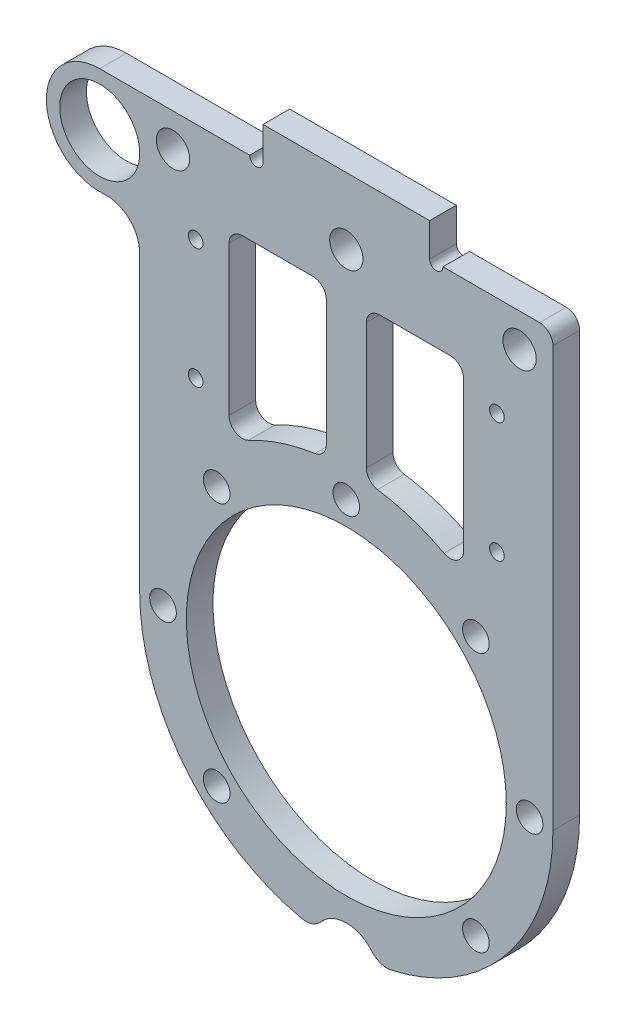
SolidWorks part; units mm, degrees
material "Thornel Mat VMA"
ref_plane "前视基准面" through (0, 0, 0) normal (0, 0, 1) x (1, 0, 0)
ref_plane "上视基准面" through (0, 0, 0) normal (0, 1, 0) x (1, 0, 0)
ref_plane "右视基准面" through (0, 0, 0) normal (1, 0, 0) x (0, 0, -1)
sketch "草图1" plane through (0, 0, 0) normal (0, 0, 1) x (1, 0, 0)
  line L0 (-31, 0) -> (-31, 44.0385)
  line L1 (-37, 65) -> (-12.5, 65)
  line L2 (31, 65) -> (31, 0)
  line L3 (0, 70) -> (0, -32.5) construction
  line L8 (12.5, 65) -> (31, 65)
  line L10 (-12.5, 65) -> (-12.5, 70)
  line L11 (-12.5, 70) -> (12.5, 70)
  line L12 (12.5, 65) -> (12.5, 70)
  line L13 (-26, 60) -> (26, 60) construction
  line L15 (-22.6, 50) -> (22.6, 50) construction
  line L16 (-22.6, 50) -> (-22.6, 32) construction
  line L17 (-22.6, 32) -> (22.6, 32) construction
  line L18 (22.6, 50) -> (22.6, 32) construction
  circle A0 centre (0, 0) radius 24
  arc A1 (-31, 0) -> (-6.7562, -30.2548) centre (0, 0) ccw
  circle A2 centre (0, 0) radius 27.5 construction
  circle A3 centre (-19.4454, 19.4454) radius 2
  circle A4 centre (0, 27.5) radius 2
  circle A5 centre (19.4454, 19.4454) radius 2
  circle A6 centre (27.5, 0) radius 2
  arc A7 (3.814, -29.2668) -> (-3.814, -29.2668) centre (0, -32.5) ccw
  arc A8 (6.7562, -30.2548) -> (31, 0) centre (0, 0) ccw
  arc A9 (3.814, -29.2668) -> (6.7562, -30.2548) centre (6.1024, -27.3269) ccw
  arc A10 (-3.814, -29.2668) -> (-6.7562, -30.2548) centre (-6.1024, -27.3269) cw
  circle A11 centre (19.4454, -19.4454) radius 2
  circle A12 centre (0, -27.5) radius 2 construction
  circle A13 centre (-19.4454, -19.4454) radius 2
  circle A14 centre (-27.5, 0) radius 2
  circle A15 centre (-26, 60) radius 2.5
  circle A16 centre (0, 60) radius 2.5
  circle A17 centre (26, 60) radius 2.5
  circle A18 centre (-22.6, 50) radius 1.1
  circle A19 centre (-22.6, 32) radius 1.1
  circle A20 centre (22.6, 32) radius 1.1
  circle A21 centre (22.6, 50) radius 1.1
  arc A22 (-37, 65) -> (-36.3846, 49.0237) centre (-37, 57) ccw
  circle A23 centre (-37, 57) radius 6
  arc A24 (-31, 44.0385) -> (-36.3846, 49.0237) centre (-36, 44.0385) ccw
  point P45 (0, 32)
  dimension "D1" = 48
  dimension "D2" = 31
  dimension "D3" = 3.5
  dimension "D4" = 4
  dimension "D8" = 5
  dimension "D10" = 3
  dimension "D11" = 25
  dimension "D12" = 5
  dimension "D13" = 5
  dimension "D14" = 5
  dimension "D15" = 45.2
  dimension "D18" = 2.2
  dimension "D19" = 12
  dimension "D20" = 2
  dimension "D21" = 5
  dimension "D6" = 52
  dimension "D7" = 65
  dimension "D9" = 32.5
  dimension "D16" = 18
  dimension "D17" = 10
  dimension "D5" = 8
extrude "凸台-拉伸1" add sketch "草图1" along normal blind 4
sketch "草图2" plane through (0, 0, 4) normal (0, 0, 1) x (1, 0, 0)
  line L0 (-12.5, 65) -> (-37, 65) construction
  line L1 (31, 65) -> (12.5, 65) construction
  circle A0 centre (-13.5, 65) radius 1
  circle A1 centre (13.5, 65) radius 1
  dimension "D1" = 2
extrude "切除-拉伸1" cut sketch "草图2" against normal through all
fillet "圆角1" [suppressed] radius 1
sketch "草图3" plane through (0, 0, 4) normal (0, 0, 1) x (1, 0, 0)
  line L0 (-17.6, 54) -> (-17.6, 26.1245)
  line L1 (0, 60) -> (0, 27.5) construction
  line L2 (-3, 60) -> (-3, 27.5)
  line L3 (3, 60) -> (3, 27.5)
  line L4 (-17.6, 54) -> (17.6, 54)
  line L5 (17.6, 54) -> (17.6, 26.1245)
  circle A0 centre (0, 0) radius 31.5
  circle A1 centre (22.6, 50) radius 1.1 construction
  circle A2 centre (-22.6, 50) radius 1.1 construction
  circle A3 centre (26, 60) radius 2.5 construction
  dimension "D1" = 63
  dimension "D5" = 5
  dimension "D4" = 5
  dimension "D6" = 6
  dimension "D2" = 3
  dimension "D3" = 3
extrude "切除-拉伸2" cut sketch "草图3" against normal blind 10 contours A0 L2 L4 L0 | A0 L5 L4 L3
fillet "圆角2" radius 2 8 edges at (-17.6, 26.1245, 2) (-17.6, 54, 2) (-3, 54, 2) (-3, 31.3568, 2) (3, 54, 2) (17.6, 54, 2) (17.6, 26.1245, 2) (3, 31.3568, 2)
fillet "圆角3" radius 2 1 edges at (31, 65, 2)
fillet "圆角4" [suppressed] radius 1
